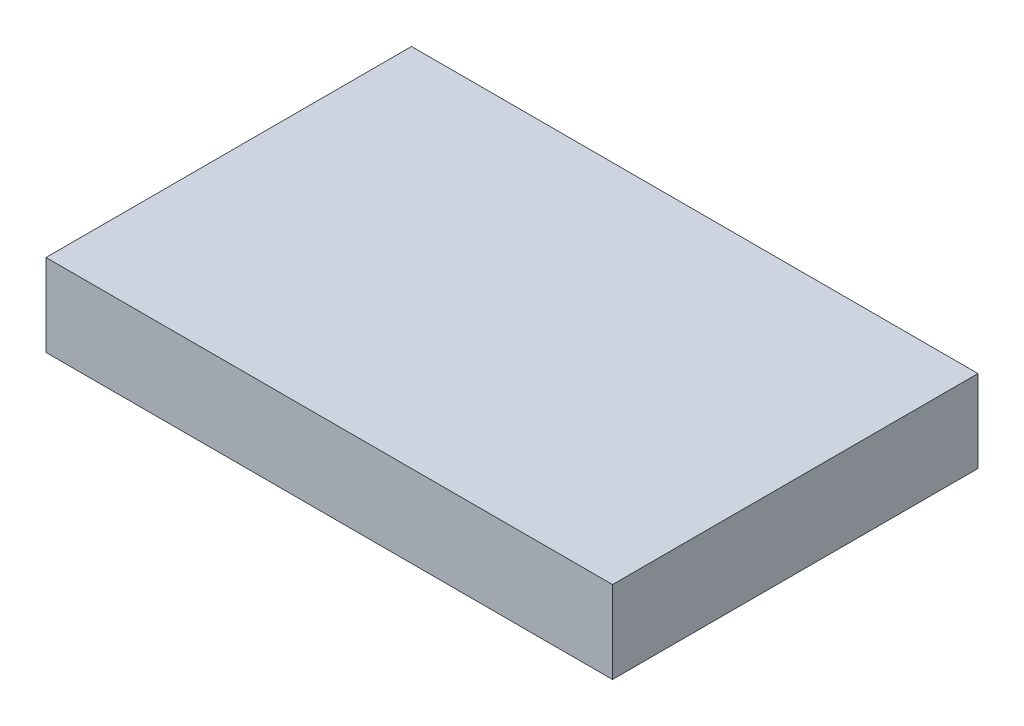
SolidWorks part; units mm, degrees
ref_plane "Front Plane" through (0, 0, 0) normal (0, 0, 1) x (1, 0, 0)
ref_plane "Top Plane" through (0, 0, 0) normal (0, 1, 0) x (1, 0, 0)
ref_plane "Right Plane" through (0, 0, 0) normal (1, 0, 0) x (0, 0, -1)
sketch "Sketch1" plane through (0, 0, 0) normal (0, 1, 0) x (1, 0, 0)
  line L1 (62, -40) -> (-62, -40)
  line L2 (62, -40) -> (62, 40)
  line L3 (62, 40) -> (-62, 40)
  line L4 (-62, -40) -> (-62, 40)
  line L5 (62, -40) -> (-62, 40) construction
  line L6 (62, 40) -> (-62, -40) construction
  point P0 (0, 0)
  dimension "D1" = 124
  dimension "D2" = 80
extrude "Boss-Extrude1" add sketch "Sketch1" along normal blind 18
sketch "Sketch2" plane through (0, 18, 0) normal (0, 1, 0) x (1, 0, 0)
  text T0 "<b>HackRF One </b>" font "Century Gothic" height in points 48
